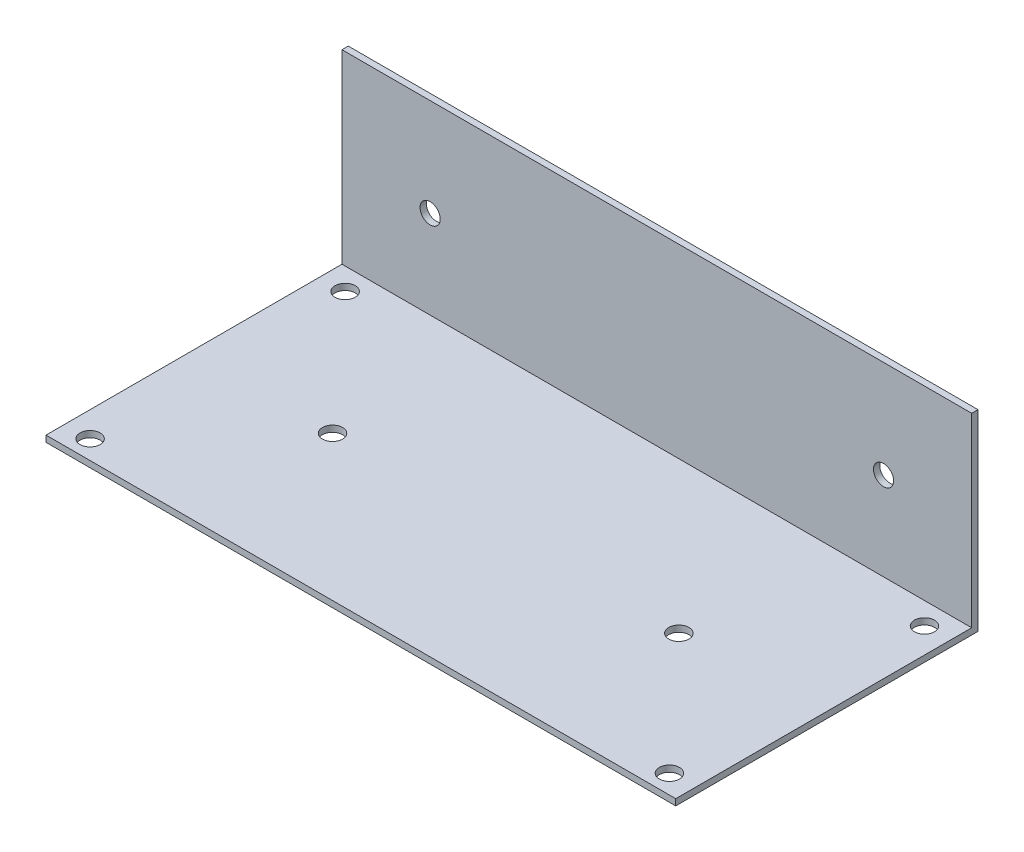
SolidWorks part; units mm, degrees
ref_plane "Спереди" through (0, 0, 0) normal (0, 0, 1) x (1, 0, 0)
ref_plane "Сверху" through (0, 0, 0) normal (0, 1, 0) x (1, 0, 0)
ref_plane "Справа" through (0, 0, 0) normal (1, 0, 0) x (0, 0, -1)
sketch "Эскиз1" plane through (0, 0, 0) normal (1, 0, 0) x (0, 0, -1)
  line L1 (0, 0) -> (-48, 0)
  line L2 (0, 0) -> (0, 30.5)
  line L3 (0, 30.5) -> (-1, 30.5)
  line L4 (-48, 0) -> (-48, 1)
  line L7 (-48, 1) -> (-1, 1)
  line L8 (-1, 30.5) -> (-1, 1)
  dimension "D1" = 48
  dimension "D2" = 30.5
  dimension "D3" = 1
  dimension "D4" = 1
extrude "Бобышка-Вытянуть1" add sketch "Эскиз1" along normal blind 100
sketch "Эскиз2" plane through (0, 0, 0) normal (0, 0, -1) x (-1, 0, 0)
  line L0 (0, 0) -> (0, 30.5) construction
  line L1 (-100, 0) -> (0, 0) construction
  line L2 (-100, 0) -> (-100, 30.5) construction
  circle A0 centre (-86, 15) radius 1.6
  circle A1 centre (-14, 15) radius 1.6
  dimension "D1" = 3.2
  dimension "D2" = 3.2
  dimension "D3" = 14
  dimension "D4" = 15
  dimension "D5" = 14
extrude "Вырез-Вытянуть1" cut sketch "Эскиз2" against normal up to surface (1 mm away) up to face at (50, 15.75, 1)
sketch "Эскиз3" plane through (0, 0, 0) normal (0, -1, 0) x (1, 0, 0)
  line L0 (0, 48) -> (0, 0) construction
  line L1 (100, 48) -> (0, 48) construction
  line L2 (100, 48) -> (100, 0) construction
  circle A0 centre (22.5, 25) radius 1.6
  circle A1 centre (77.5, 25) radius 1.6
  dimension "D1" = 3.2
  dimension "D2" = 3.2
  dimension "D3" = 22.5
  dimension "D4" = 23
  dimension "D5" = 22.5
extrude "Вырез-Вытянуть2" cut sketch "Эскиз3" against normal up to surface (1 mm away) up to face at (50, 1, 24.5)
sketch "Sketch1" plane through (0, 0, 0) normal (0, -1, 0) x (1, 0, 0)
  line L0 (0, 48) -> (0, 0) construction
  line L2 (100, 48) -> (0, 48) construction
  line L5 (100, 48) -> (100, 0) construction
  line L6 (100, 0) -> (0, 0) construction
  circle A4 centre (4, 45) radius 1.6
  circle A5 centre (96, 45) radius 1.6
  circle A6 centre (96, 4.5) radius 1.6
  circle A7 centre (4, 4.5) radius 1.6
  dimension "D3" = 2
  dimension "D4" = 4
  dimension "D5" = 3
  dimension "D6" = 4
  dimension "D7" = 4.5
  dimension "D8" = 4
  dimension "D1" = 3.2
  dimension "D2" = 2
extrude "Cut-Extrude1" cut sketch "Sketch1" against normal blind 10
